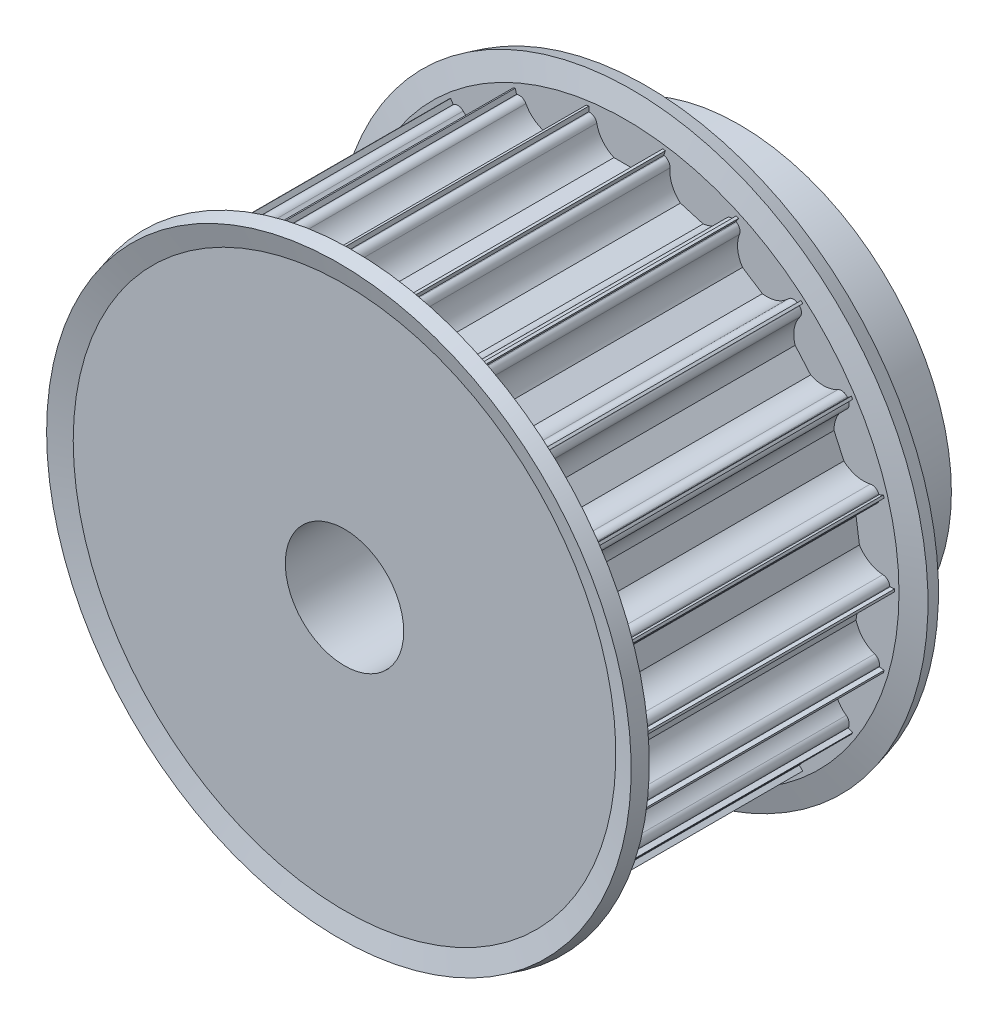
SolidWorks part; units mm, degrees
ref_plane "Front Plane" through (0, 0, 0) normal (0, 0, 1) x (1, 0, 0)
ref_plane "Top Plane" through (0, 0, 0) normal (0, 1, 0) x (1, 0, 0)
ref_plane "Right Plane" through (0, 0, 0) normal (1, 0, 0) x (0, 0, -1)
sketch "Sketch1" plane through (0, 0, 0) normal (1, 0, 0) x (0, 0, -1)
  line L0 (0, 4.4564) -> (24.6246, 4.4564) construction
  line L1 (0, 10.4564) -> (40, 10.4564)
  line L2 (40, 10.4564) -> (40, 25.9564)
  line L3 (40, 25.9564) -> (30, 25.9564)
  line L4 (30, 25.9564) -> (30, 31.7064)
  line L5 (30, 31.7064) -> (0, 31.7064)
  line L6 (0, 31.7064) -> (0, 10.4564)
  dimension "D1" = 27.25
  dimension "D2" = 30
  dimension "D3" = 6
  dimension "D4" = 40
  dimension "D5" = 10
  dimension "D6" = 15.5
  dimension "D7" = 6
revolve "Revolve1" add sketch "Sketch1" angle 360 about L0
sketch "Sketch2" plane through (0, 0, 0) normal (0, 0, 1) x (1, 0, 0)
  line L0 (0, 31.7064) -> (0, -22.7936) construction
  line L1 (-3.6742, 30.9564) -> (-3.75, 30.9564)
  line L2 (-3.75, 30.9564) -> (-3.75, 32.9564)
  line L3 (-3.75, 32.9564) -> (3.75, 32.9564)
  line L4 (3.75, 32.9564) -> (3.75, 30.9564)
  line L5 (3.75, 30.9564) -> (3.6742, 30.9564)
  line L6 (-1.199, 28.2064) -> (1.199, 28.2064)
  arc A0 (2.9394, 30.3564) -> (1.199, 28.2064) centre (0, 30.9564) cw
  circle A1 centre (0, 4.4564) radius 27.25 construction
  arc A2 (2.9394, 30.3564) -> (3.6742, 30.9564) centre (3.6742, 30.2064) cw
  arc A3 (-2.9394, 30.3564) -> (-3.6742, 30.9564) centre (-3.6742, 30.2064) ccw
  arc A4 (-1.199, 28.2064) -> (-2.9394, 30.3564) centre (0, 30.9564) cw
  point P9 (0, 4.4564)
  point P15 (0, 32.9564)
  point P18 (3, 30.9564)
  point P21 (-3, 30.9564)
  dimension "D1" = 3
  dimension "D5" = 0.75
  dimension "D2" = 26.5
  dimension "D3" = 7.5
  dimension "D4" = 2
  dimension "D6" = 2.75
extrude "Cut-Extrude1" cut sketch "Sketch2" against normal up to next
pattern_circular "CirPattern1" count 22 over 360 about axis through (0, 4.4564, 0) along (0, 0, 1) of "Cut-Extrude1"
sketch "Sketch3" plane through (0, 0, 0) normal (1, 0, 0) x (0, 0, -1)
  line L0 (15, 31.4103) -> (15, 17.8894) construction
  line L1 (30, 31.4103) -> (0, 31.4103) construction
  line L2 (30, 17.8894) -> (0, 17.8894) construction
  line L3 (30, 25.9564) -> (30, 31.9489)
  line L4 (30, 31.9489) -> (30.5701, 34.0764)
  line L5 (30.5701, 34.0764) -> (29.1212, 34.4646)
  line L6 (29.1212, 34.4646) -> (28.5, 32.1464)
  line L7 (28.5, 32.1464) -> (28.5, 25.9564)
  line L8 (28.5, 25.9564) -> (30, 25.9564)
  line L9 (40, 25.9564) -> (30, 25.9564) construction
  line L10 (1.5, 32.1464) -> (1.5, 25.9564)
  line L11 (0.8788, 34.4646) -> (1.5, 32.1464)
  line L12 (-0.5701, 34.0764) -> (0.8788, 34.4646)
  line L13 (0, 31.9489) -> (-0.5701, 34.0764)
  line L14 (0, 25.9564) -> (0, 31.9489)
  line L15 (1.5, 25.9564) -> (0, 25.9564)
  line L16 (15, 31.4103) -> (15, -22.4975) construction
  line L17 (0, -22.4975) -> (30, -22.4975) construction
  line L18 (15, 4.4564) -> (-17.187, 4.4564) construction
  dimension "D1" = 15
  dimension "D2" = 1.5
  dimension "D3" = 6.19
  dimension "D4" = 2.4
revolve "Revolve3" add sketch "Sketch3" angle 360 about L18
